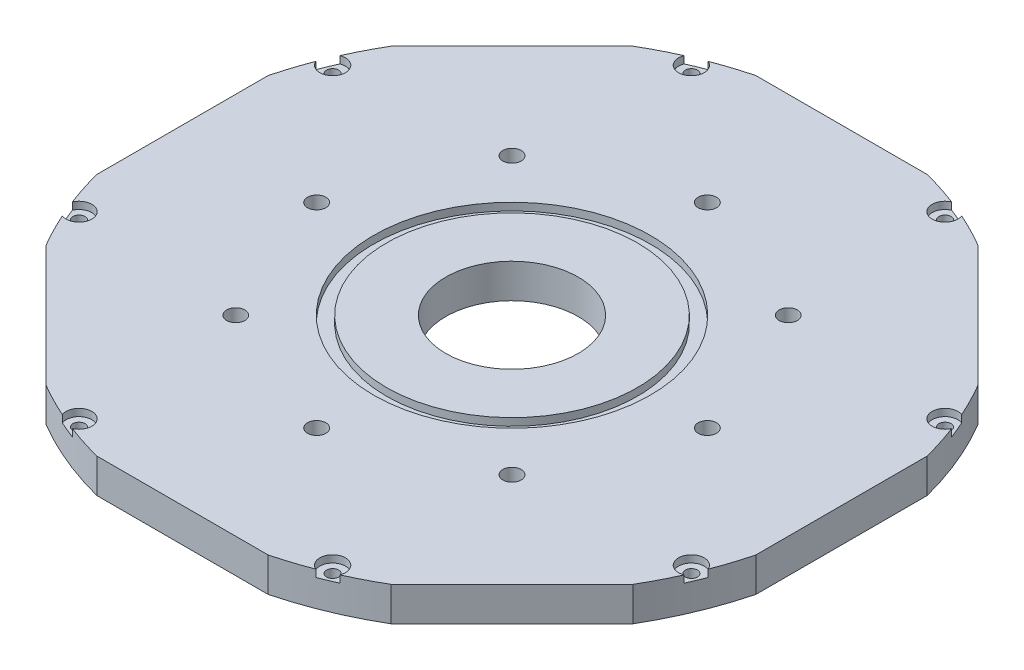
SolidWorks part; units mm, degrees
other "Markup1"
sketch "Sketch46" plane through (-122.3, 0, 122.3) normal (-0.1263, -0.9546, 0.2699) x (-0.172, -0.2469, -0.9537)
material "6061-T6 (SS)"
ref_plane "Front Plane" through (0, 0, 0) normal (0, 0, 1) x (1, 0, 0)
ref_plane "Top Plane" through (0, 0, 0) normal (0, 1, 0) x (1, 0, 0)
ref_plane "Right Plane" through (0, 0, 0) normal (1, 0, 0) x (0, 0, -1)
sketch "Sketch1" plane through (0, 0, 0) normal (0, 1, 0) x (1, 0, 0)
  line L1 (-50.6583, 122.3) -> (-122.3, 50.6583)
  line L2 (-122.3, 50.6583) -> (-122.3, -50.6583)
  line L3 (-122.3, -50.6583) -> (-50.6583, -122.3)
  line L4 (-50.6583, -122.3) -> (50.6583, -122.3)
  line L5 (50.6583, -122.3) -> (122.3, -50.6583)
  line L6 (122.3, -50.6583) -> (122.3, 50.6583)
  line L7 (122.3, 50.6583) -> (50.6583, 122.3)
  line L8 (50.6583, 122.3) -> (-50.6583, 122.3)
  circle A0 centre (0, 0) radius 122.3 construction
  circle A1 centre (0, 0) radius 126.365
  dimension "D2" = 252.73
  dimension "D1" = 244.6
extrude "Boss-Extrude1" add sketch "Sketch1" along normal blind 12.7 contours L4 A1 L5 L6 L7 L8 L1 L2 L3
sketch "Sketch3" plane through (0, 12.7, 0) normal (0, 1, 0) x (1, 0, 0)
  circle A0 centre (0, 0) radius 24.5745
  dimension "D1" = 49.149
extrude "Cut-Extrude1" cut sketch "Sketch3" against normal through all contours A0
sketch "Sketch5" plane through (0, 12.7, 0) normal (0, 1, 0) x (1, 0, 0)
  circle A0 centre (0, 0) radius 46.5455
  circle A1 centre (0, 0) radius 51.3715
  dimension "D1" = 93.091
  dimension "D2" = 102.743
extrude "Cut-Extrude2" cut sketch "Sketch5" against normal blind 2.794
sketch "Sketch19" plane through (0, 12.7, 0) normal (0, 1, 0) x (1, 0, 0)
  line L5 (-63.9978, 108.9605) -> (-31.7934, 122.3) construction
  line L6 (-47.8956, 115.6303) -> (-43.6974, 105.4949) construction
  circle A4 centre (0, 0) radius 122.9995
  circle A5 centre (-47.0699, 113.6367) radius 2.2479
  dimension "D1" = 4.4958
  dimension "D3" = 245.999
sketch "Sketch21" plane through (0, 12.7, 0) normal (0, 1, 0) x (1, 0, 0)
  point P0 (-72.5, 0)
  dimension "D1" = 72.5
hole_wizard "M8x1.25 Tapped Hole1" positions "Sketch22" profile "Sketch23" tap size "M8x1.25" standard "ANSI Metric"
sketch "Sketch22" plane through (0, 12.7, 0) normal (0, 1, 0) x (1, 0, 0)
  point P0 (-72.5, 0)
sketch "Sketch23" plane through (-72.5, 12.7, 0) normal (1, 0, 0) x (0, 0, 1)
  line L0 (0, 0) -> (0, 8.3929)
  line L1 (0, 8.3929) -> (3.4, 6.35)
  line L2 (3.4, 6.35) -> (3.4, 0)
  line L5 (3.4, 0) -> (0, 0)
  line L10 (0, 8.3929) -> (-3.4, 6.35) construction
  line L11 (0, -6.35) -> (0, 107.95) construction
  dimension "Tap Drill Dia." = 6.8
  dimension "Tap Drill Depth" = 6.35
  dimension "Drill Angle" = 118
cosmetic thread "Hole Thread2" parameters "D1"=6.35, "D2"=8
sketch "Sketch33" [suppressed] plane through (0, 19.05, 0) normal (0, 1, 0) x (1, 0, 0)
  circle A0 centre (-71.374, 0) radius 3.9687
  dimension "D1" = 7.9375
sketch "Sketch37" plane through (0, 0, 0) normal (0, -1, 0) x (1, 0, 0)
  circle A0 centre (0, 0) radius 119.0625
  circle A1 centre (0, 0) radius 115.2525
  dimension "D1" = 238.125
  dimension "D2" = 230.505
extrude "Cut-Extrude7" [suppressed] cut sketch "Sketch37" against normal blind 2.667
pattern_circular "CirPattern4" count 8 over 360 about axis through (0, 0, 0) along (0, 1, 0) of "M8x1.25 Tapped Hole1"
cosmetic thread "Hole Thread3" parameters "D1"=6.35, "D2"=8
cosmetic thread "Hole Thread4" parameters "D1"=6.35, "D2"=8
cosmetic thread "Hole Thread5" parameters "D1"=6.35, "D2"=8
cosmetic thread "Hole Thread6" parameters "D1"=6.35, "D2"=8
cosmetic thread "Hole Thread7" parameters "D1"=6.35, "D2"=8
cosmetic thread "Hole Thread8" parameters "D1"=6.35, "D2"=8
cosmetic thread "Hole Thread9" parameters "D1"=6.35, "D2"=8
hole_wizard "CBORE for #8 Binding Head Machine Screw2" positions "Sketch47" profile "Sketch49" counterbore size "#8" standard "ANSI Inch" end condition through all
sketch "Sketch47" plane through (0, 12.7, 0) normal (0, 1, 0) x (1, 0, 0)
  point P0 (-47.0699, 113.6367)
sketch "Sketch49" plane through (-47.0699, 12.7, -113.6367) normal (1, 0, 0) x (0, 0, 1)
  line L0 (0, 0) -> (0, 12.7)
  line L1 (0, 12.7) -> (2.2479, 12.7)
  line L3 (2.2479, 12.7) -> (2.2479, 2.667)
  line L4 (2.2479, 2.667) -> (4.7625, 2.667)
  line L5 (4.7625, 2.667) -> (4.7625, 0)
  line L7 (4.7625, 0) -> (0, 0)
  line L11 (0, -6.35) -> (0, 107.95) construction
  dimension "Thru Hole Dia." = 4.4958
  dimension "Thru Hole Depth" = 12.7
  dimension "C'Bore Dia." = 9.525
  dimension "C'Bore Depth" = 2.667
pattern_circular "CirPattern5" count 8 over 360 about axis through (0, 0, 0) along (0, 1, 0) of "CBORE for #8 Binding Head Machine Screw2"
